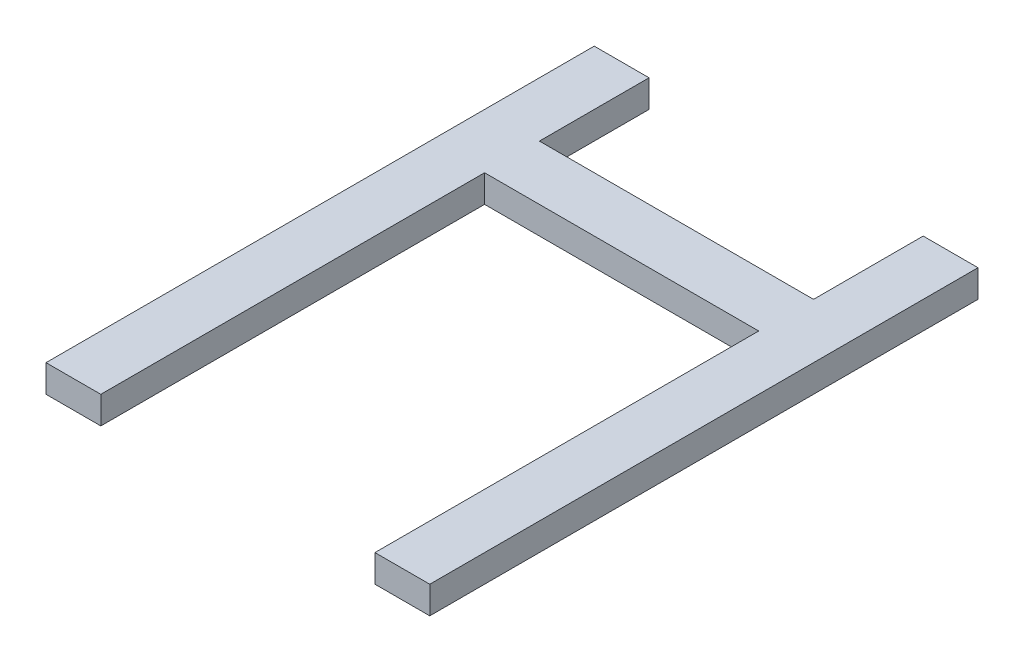
SolidWorks part; units mm, degrees
ref_plane "Plan de face" through (0, 0, 0) normal (0, 0, 1) x (1, 0, 0)
ref_plane "Plan de dessus" through (0, 0, 0) normal (0, 1, 0) x (1, 0, 0)
ref_plane "Plan de droite" through (0, 0, 0) normal (1, 0, 0) x (0, 0, -1)
sketch "Esquisse1" plane through (0, 0, 0) normal (0, 1, 0) x (1, 0, 0)
  line L1 (-25, -5) -> (25, -5)
  line L2 (-25, -5) -> (-25, 5)
  line L3 (-25, 5) -> (25, 5)
  line L4 (25, -5) -> (25, 5)
  line L5 (-25, -5) -> (25, 5) construction
  line L6 (-25, 5) -> (25, -5) construction
  line L7 (25, 25) -> (35, 25)
  line L8 (25, 25) -> (25, -75)
  line L9 (25, -75) -> (35, -75)
  line L10 (35, 25) -> (35, -75)
  line L11 (-35, 25) -> (-25, 25)
  line L12 (-35, 25) -> (-35, -75)
  line L13 (-35, -75) -> (-25, -75)
  line L14 (-25, 25) -> (-25, -75)
  point P0 (0, 0)
  point P14 (-30, 25)
  dimension "D1" = 10
  dimension "D2" = 100
  dimension "D3" = 50
  dimension "D4" = 10
  dimension "D5" = 20
extrude "Boss.-Extru.1" add sketch "Esquisse1" along normal blind 5 contours L14 L11 L12 L13 L2 | L1 L4 L3 L2 | L10 L7 L8 L4 L9
